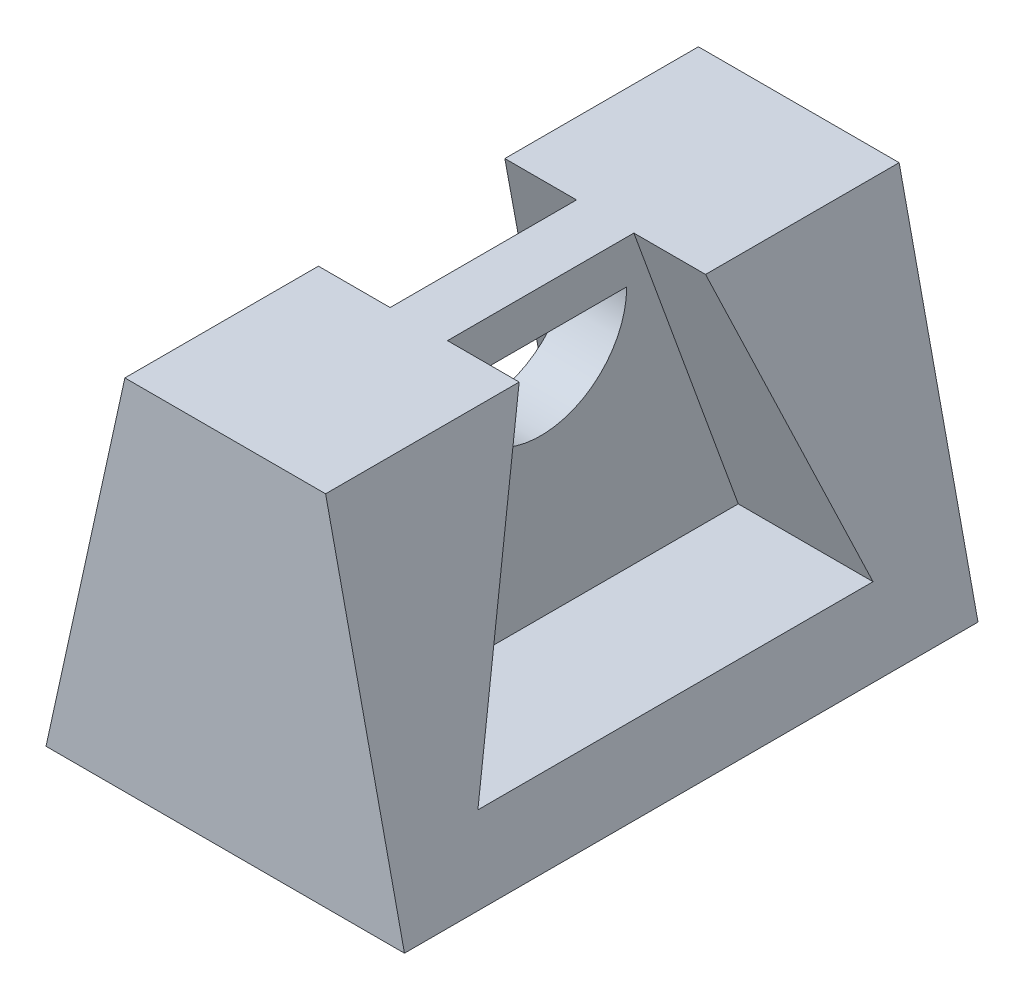
SolidWorks part; units mm, degrees
ref_plane "前视基准面" through (0, 0, 0) normal (0, 0, 1) x (1, 0, 0)
ref_plane "上视基准面" through (0, 0, 0) normal (0, 1, 0) x (1, 0, 0)
ref_plane "右视基准面" through (0, 0, 0) normal (1, 0, 0) x (0, 0, -1)
other "Configuration Table"
sketch "草图3" plane through (0, 0, 0) normal (0, 0, 1) x (1, 0, 0)
  line L0 (0, 53.499) -> (0, -49.9493) construction
  line L1 (14, 42.6471) -> (-14, 42.6471)
  line L2 (-14, 42.6471) -> (-25, -7.3529)
  line L3 (-25, -7.3529) -> (25, -7.3529)
  line L4 (14, 42.6471) -> (25, -7.3529)
  point P8 (0, -7.3529)
  point P9 (0, 42.6471)
  dimension "D1" = 50
  dimension "D2" = 14
  dimension "D3" = 25
extrude "凸台-拉伸1" add sketch "草图3" along normal mid plane 80
sketch "草图4" plane through (0, 0, 0) normal (1, 0, 0) x (0, 0, -1)
  line L0 (0, -10.2258) -> (0, 45.0758) construction
  line L1 (13, 42.6471) -> (-13, 42.6471)
  line L2 (-40, 42.6471) -> (40, 42.6471) construction
  line L3 (-13, 42.6471) -> (-27.5588, 2.6471)
  line L4 (-27.5588, 2.6471) -> (27.5588, 2.6471)
  line L5 (13, 42.6471) -> (27.5588, 2.6471)
  point P10 (0, 42.6471)
  point P11 (0, 2.6471)
  dimension "D1" = 70
  dimension "D2" = 13
  dimension "D3" = 40
extrude "切除-拉伸2" cut sketch "草图4" against normal blind 50 from offset 4 offset against normal yes
mirror "镜向1" about plane through (0, 0, 0) normal (1, 0, 0) of "切除-拉伸2"
sketch "草图6" plane through (-4, 0, 0) normal (-1, 0, 0) x (0, 0, 1)
  line L0 (-12, 36.6471) -> (12, 36.6471)
  line L1 (-13, 42.6471) -> (13, 42.6471) construction
  line L2 (0, 0) -> (0, 42.3711) construction
  arc A0 (-12, 36.6471) -> (12, 36.6471) centre (0, 36.6471) ccw
  point P8 (0, 0)
  dimension "D2" = 12
  dimension "D1" = 6
extrude "切除-拉伸3" cut sketch "草图6" against normal up to surface (8 mm away) up to face at (4, 22.6471, 0)
